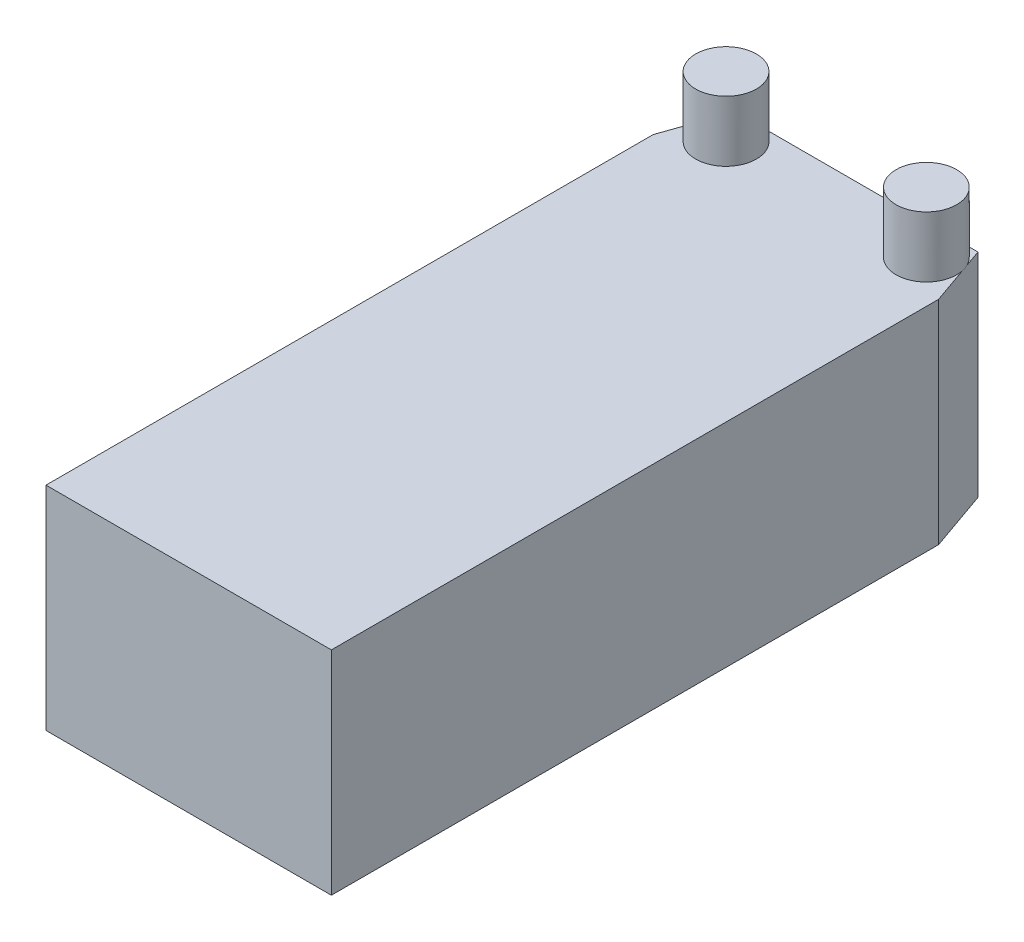
SolidWorks part; units mm, degrees
ref_plane "前视基准面" through (0, 0, 0) normal (0, 0, 1) x (1, 0, 0)
ref_plane "上视基准面" through (0, 0, 0) normal (0, 1, 0) x (1, 0, 0)
ref_plane "右视基准面" through (0, 0, 0) normal (1, 0, 0) x (0, 0, -1)
sketch "草图1" plane through (0, 0, 0) normal (0, 1, 0) x (1, 0, 0)
  line L0 (-23.5, 50) -> (-20, 60)
  line L1 (-23.5, -50) -> (23.5, -50)
  line L2 (-23.5, -50) -> (-23.5, 50)
  line L4 (23.5, -50) -> (23.5, 50)
  line L5 (-23.5, -50) -> (23.5, 50) construction
  line L6 (-23.5, 50) -> (23.5, -50) construction
  line L7 (-20, 60) -> (20, 60)
  line L8 (20, 60) -> (23.5, 50)
  point P1 (0, 0)
  point P8 (0, 60)
  dimension "D1" = 47
  dimension "D2" = 100
  dimension "D4" = 40
extrude "凸台-拉伸1" add sketch "草图1" along normal blind 35
sketch "草图2" plane through (0, 35, 0) normal (0, 1, 0) x (1, 0, 0)
  line L0 (20, 60) -> (-20, 60) construction
  line L1 (-23.5, 50) -> (-23.5, -50) construction
  line L2 (23.5, -50) -> (23.5, 50) construction
  circle A0 centre (-16.5, 55) radius 5
  circle A1 centre (16.5, 55) radius 5
  dimension "D1" = 10
  dimension "D2" = 5
  dimension "D3" = 7
  dimension "D4" = 7
extrude "凸台-拉伸2" add sketch "草图2" along normal blind 10
